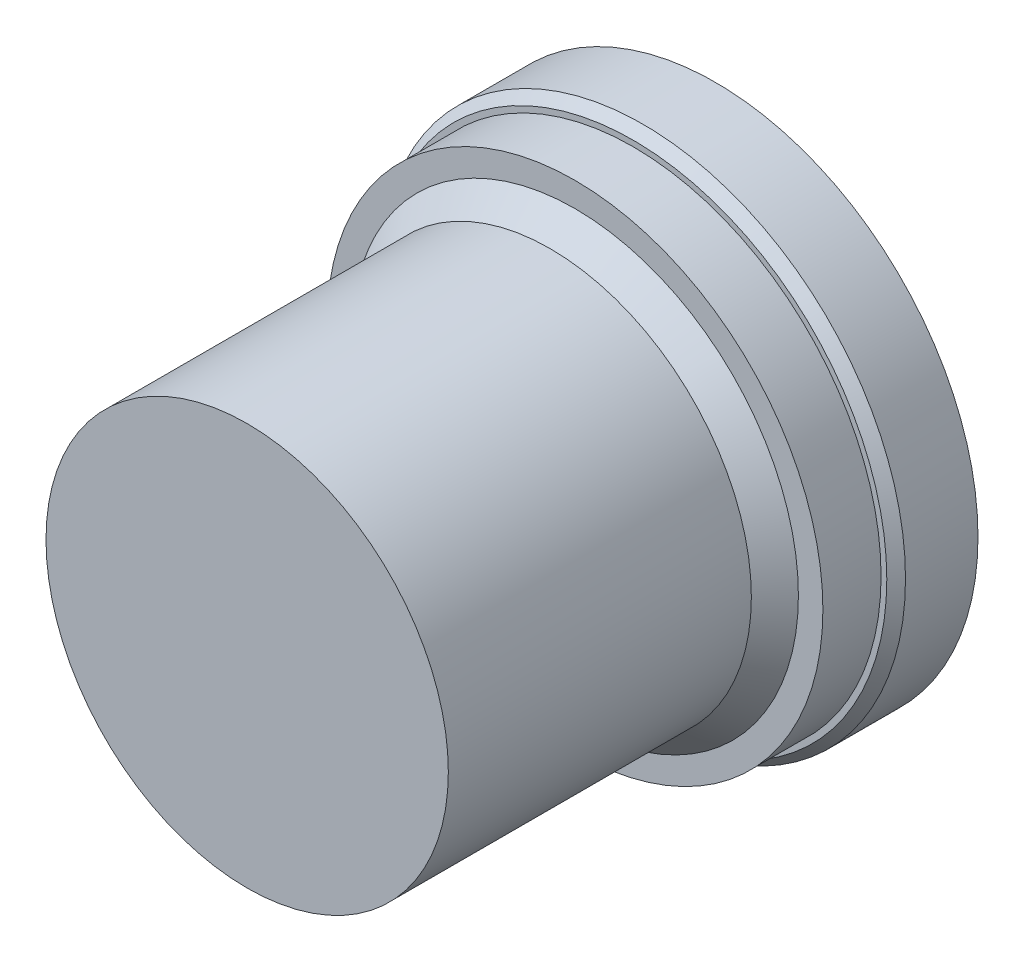
SolidWorks part; units mm, degrees
ref_plane "Front Plane" through (0, 0, 0) normal (0, 0, 1) x (1, 0, 0)
ref_plane "Top Plane" through (0, 0, 0) normal (0, 1, 0) x (1, 0, 0)
ref_plane "Right Plane" through (0, 0, 0) normal (1, 0, 0) x (0, 0, -1)
sketch "Sketch3" plane through (0, 0, 0) normal (1, 0, 0) x (0, 0, -1)
  line L0 (-72.6353, 0) -> (80.8641, 0) construction
  line L1 (40.8277, 0) -> (40.8277, 20.9677)
  line L2 (35.0365, 20.9677) -> (34.2491, 20.2611)
  line L3 (34.2491, 20.2611) -> (34.2491, 19.8039)
  line L4 (29.6009, 19.8039) -> (29.6009, 17.8481)
  line L5 (29.6009, 17.8481) -> (27.6197, 16.0701)
  line L6 (27.6197, 16.0701) -> (3.4135, 16.0701)
  line L7 (3.4135, 16.0701) -> (3.4135, 0)
  line L8 (35.0365, 20.9677) -> (40.8277, 20.9677)
  line L9 (34.2491, 19.8039) -> (29.6009, 19.8039)
  line L10 (40.8277, 0) -> (3.4135, 0)
  dimension "D1" = 20.9677
  dimension "D2" = 5.7912
  dimension "D3" = 0.7874
  dimension "D4" = 0.4572
  dimension "D5" = 4.6482
  dimension "D6" = 1.9558
  dimension "D7" = 1.778
  dimension "D8" = 1.9812
  dimension "D9" = 24.2062
revolve "Revolve1" add sketch "Sketch3" angle 360 about L0
